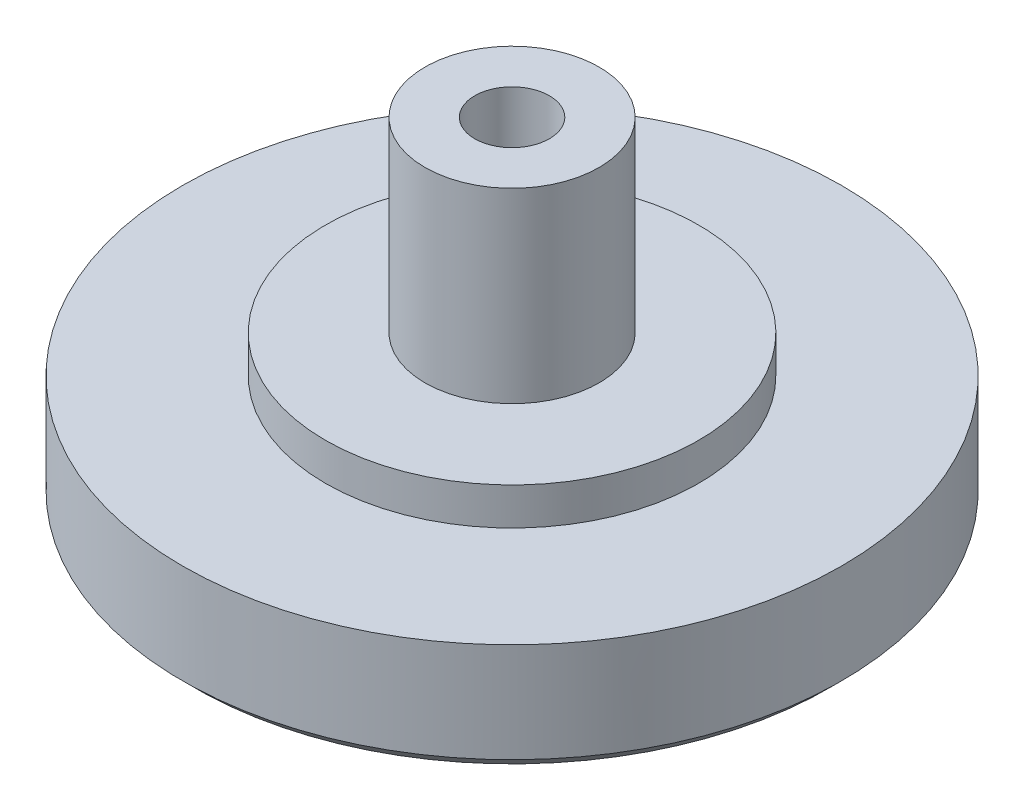
SolidWorks part; units mm, degrees
ref_plane "Front Plane" through (0, 0, 0) normal (0, 0, 1) x (1, 0, 0)
ref_plane "Top Plane" through (0, 0, 0) normal (0, 1, 0) x (1, 0, 0)
ref_plane "Right Plane" through (0, 0, 0) normal (1, 0, 0) x (0, 0, -1)
sketch "Croquis2" plane through (0, 0, 0) normal (0, 1, 0) x (1, 0, 0)
  circle A0 centre (0, 0) radius 26.5
extrude "Saliente-Extruir1" add sketch "Croquis2" along normal blind 8
sketch "Croquis3" plane through (0, 0, 0) normal (0, -1, 0) x (-1, 0, 0)
  circle A0 centre (0, 0) radius 26.5
extrude "Saliente-Extruir2" add sketch "Croquis3" along normal blind 1 draft 45
sketch "Croquis4" plane through (0, -1, 0) normal (0, -1, 0) x (-1, 0, 0)
  circle A0 centre (0, 0) radius 17.5
extrude "Saliente-Extruir3" add sketch "Croquis4" along normal blind 1
sketch "Croquis5" plane through (0, 8, 0) normal (0, 1, 0) x (1, 0, 0)
  circle A0 centre (0, 0) radius 15
  point P3 (0, 0)
extrude "Saliente-Extruir4" add sketch "Croquis5" along normal blind 3
sketch "Croquis6" plane through (0, 11, 0) normal (0, 1, 0) x (1, 0, 0)
  circle A0 centre (0, 0) radius 7
extrude "Saliente-Extruir5" add sketch "Croquis6" along normal blind 15
sketch "Croquis7" plane through (0, 26, 0) normal (0, 1, 0) x (1, 0, 0)
  circle A0 centre (0, 0) radius 3
extrude "Cortar-Extruir1" cut sketch "Croquis7" against normal blind 9
